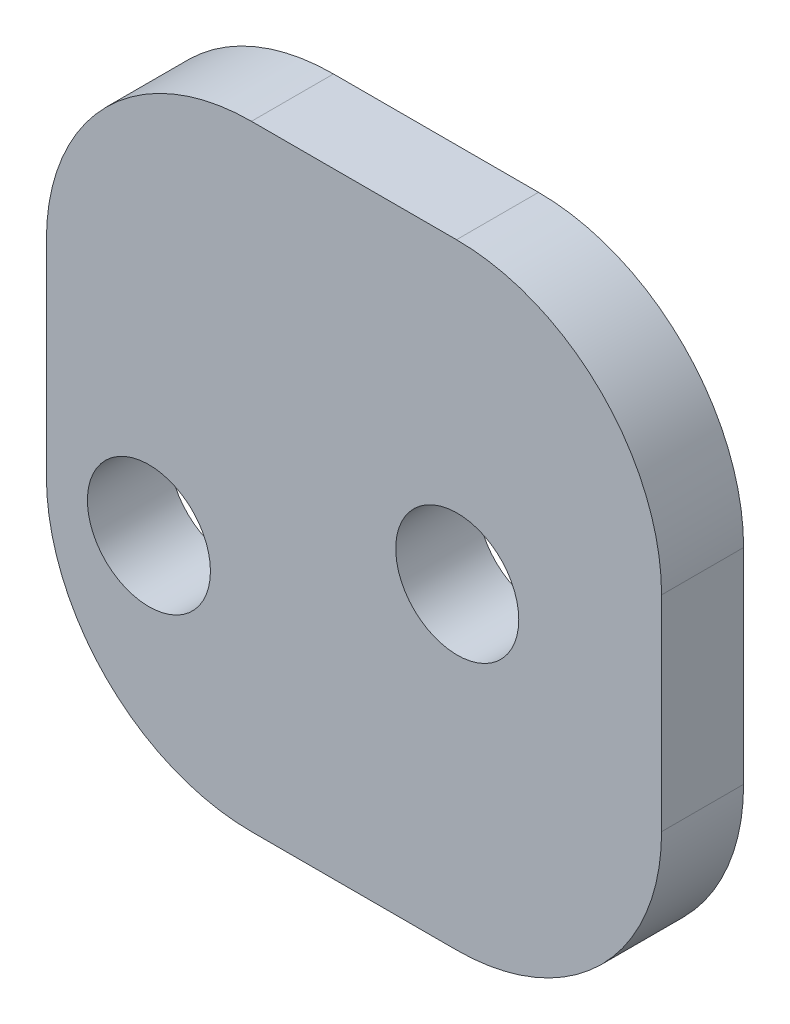
SolidWorks part; units mm, degrees
material "Thornel Mat VMA"
ref_plane "前视基准面" through (0, 0, 0) normal (0, 0, 1) x (1, 0, 0)
ref_plane "上视基准面" through (0, 0, 0) normal (0, 1, 0) x (1, 0, 0)
ref_plane "右视基准面" through (0, 0, 0) normal (1, 0, 0) x (0, 0, -1)
sketch "草图1" plane through (0, 0, 0) normal (0, 0, 1) x (1, 0, 0)
  line L1 (-20, -7.5) -> (20, -7.5)
  line L2 (-20, -7.5) -> (-20, 7.5)
  line L3 (-20, 7.5) -> (20, 7.5)
  line L4 (20, -7.5) -> (20, 7.5)
  line L5 (-20, -7.5) -> (20, 7.5) construction
  line L6 (-20, 7.5) -> (20, -7.5) construction
  point P0 (0, 0)
  dimension "D1" = 40
  dimension "D2" = 15
extrude "凸台-拉伸1" add sketch "草图1" along normal blind 2
sketch "草图3" plane through (0, 0, 2) normal (0, 0, 1) x (1, 0, 0)
  circle A0 centre (-9.9825, 0.2362) radius 1.5 construction
  circle A1 centre (-17.5, -2.5) radius 1.5 construction
  circle A2 centre (-9.9825, 0.2362) radius 1.5
  circle A3 centre (-17.5, -2.5) radius 1.5
extrude "切除-拉伸1" cut sketch "草图3" against normal blind 2
sketch "草图6" plane through (0, 0, 2) normal (0, 0, 1) x (1, 0, 0)
  line L0 (-5, 7.5) -> (-5, -7.5)
  line L1 (20, 7.5) -> (-20, 7.5) construction
  line L2 (-20, -7.5) -> (20, -7.5) construction
  line L3 (-5, -7.5) -> (36.1489, -18.4952)
  line L4 (36.1489, -18.4952) -> (30.7816, 18.5436)
  line L5 (30.7816, 18.5436) -> (-5, 7.5)
  line L6 (-20, 7.5) -> (-20, -7.5) construction
  dimension "D1" = 15
extrude "切除-拉伸2" cut sketch "草图6" against normal blind 10
fillet "圆角1" radius 5 4 edges at (-20, -7.5, 1) (-5, 7.5, 1) (-5, -7.5, 1) (-20, 7.5, 1)
